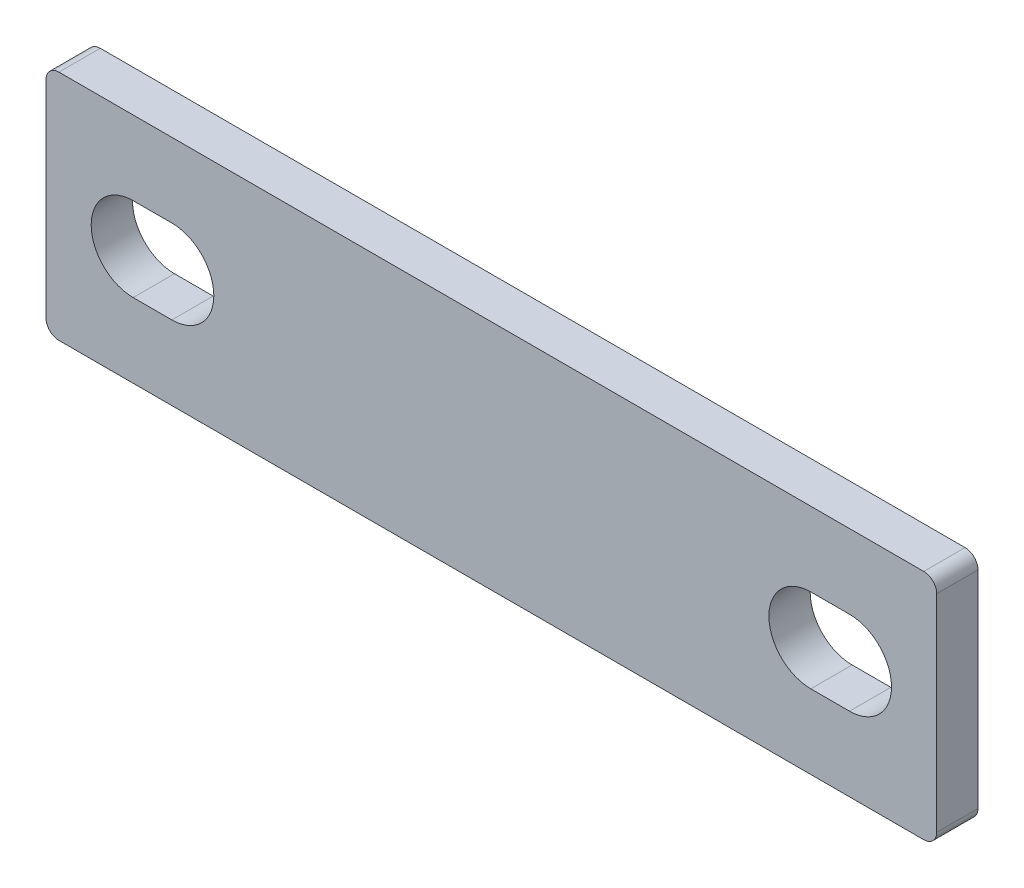
SolidWorks part; units mm, degrees
material "PET"
ref_plane "Piano frontale" through (0, 0, 0) normal (0, 0, 1) x (1, 0, 0)
ref_plane "Piano superiore" through (0, 0, 0) normal (0, 1, 0) x (1, 0, 0)
ref_plane "Piano destro" through (0, 0, 0) normal (1, 0, 0) x (0, 0, -1)
sketch "Schizzo1" plane through (0, 0, 0) normal (0, 0, 1) x (1, 0, 0)
  line L0 (0, -34) -> (0, -2) construction
  line L1 (-2, 0) -> (-40, 0) construction
  line L3 (-40, -36) -> (-2, -36) construction
  line L4 (-98, 0) -> (-136, 0) construction
  line L5 (-138, -2) -> (-138, -34) construction
  line L6 (-136, -36) -> (-98, -36) construction
  line L8 (0, -34) -> (0, -2)
  line L9 (-2, 0) -> (-40, 0)
  line L11 (-40, -36) -> (-2, -36)
  line L12 (-98, 0) -> (-136, 0)
  line L13 (-138, -2) -> (-138, -34)
  line L14 (-136, -36) -> (-98, -36)
  line L16 (-98, 0) -> (-40, 0)
  line L17 (-98, -36) -> (-40, -36)
  line L18 (-19.5, -24.5) -> (-13.5, -24.5) construction
  line L19 (-13.5, -11.5) -> (-19.5, -11.5) construction
  line L20 (-124.5, -24.5) -> (-118.5, -24.5) construction
  line L21 (-118.5, -11.5) -> (-124.5, -11.5) construction
  line L22 (-19.5, -24.5) -> (-13.5, -24.5)
  line L23 (-13.5, -11.5) -> (-19.5, -11.5)
  line L24 (-124.5, -24.5) -> (-118.5, -24.5)
  line L25 (-118.5, -11.5) -> (-124.5, -11.5)
  arc A0 (0, -2) -> (-2, 0) centre (-2, -2) ccw construction
  arc A1 (-2, -36) -> (0, -34) centre (-2, -34) ccw construction
  arc A2 (-136, 0) -> (-138, -2) centre (-136, -2) ccw construction
  arc A3 (-138, -34) -> (-136, -36) centre (-136, -34) ccw construction
  arc A4 (0, -2) -> (-2, 0) centre (-2, -2) ccw
  arc A5 (-2, -36) -> (0, -34) centre (-2, -34) ccw
  arc A6 (-136, 0) -> (-138, -2) centre (-136, -2) ccw
  arc A7 (-138, -34) -> (-136, -36) centre (-136, -34) ccw
  arc A8 (-13.5, -24.5) -> (-13.5, -11.5) centre (-13.5, -18) ccw construction
  arc A9 (-19.5, -11.5) -> (-19.5, -24.5) centre (-19.5, -18) ccw construction
  arc A10 (-124.5, -11.5) -> (-124.5, -24.5) centre (-124.5, -18) ccw construction
  arc A11 (-118.5, -24.5) -> (-118.5, -11.5) centre (-118.5, -18) ccw construction
  arc A12 (-13.5, -24.5) -> (-13.5, -11.5) centre (-13.5, -18) ccw
  arc A13 (-19.5, -11.5) -> (-19.5, -24.5) centre (-19.5, -18) ccw
  arc A14 (-124.5, -11.5) -> (-124.5, -24.5) centre (-124.5, -18) ccw
  arc A15 (-118.5, -24.5) -> (-118.5, -11.5) centre (-118.5, -18) ccw
extrude "Estrusione-Estrusione1" add sketch "Schizzo1" along normal up to surface (6.4 mm away)
